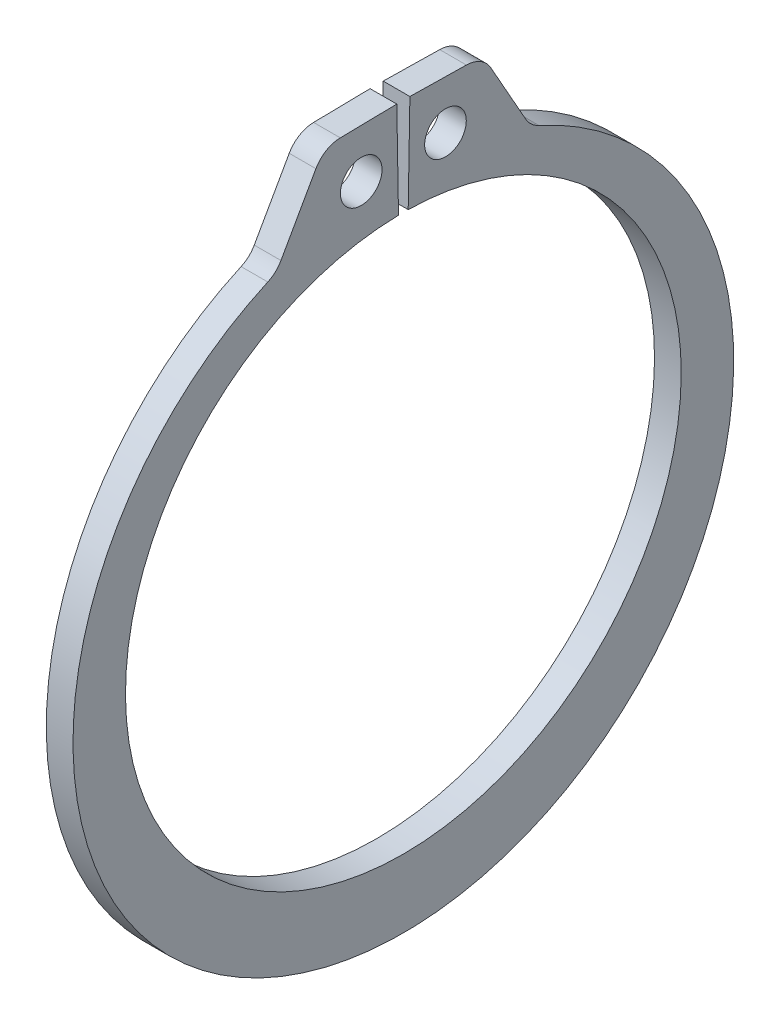
SolidWorks part; units mm, degrees
material "Cast Carbon Steel"
ref_plane "Front" through (0, 0, 0) normal (0, 0, 1) x (1, 0, 0)
ref_plane "Top" through (0, 0, 0) normal (0, 1, 0) x (1, 0, 0)
ref_plane "Right" through (0, 0, 0) normal (1, 0, 0) x (0, 0, -1)
sketch "Sketch1" plane through (0, 0, 0) normal (1, 0, 0) x (0, 0, -1)
  line L0 (0, 0) -> (0, 13.2207) construction
  line L1 (-0.2307, 13.2187) -> (-0.3114, 17.8408)
  line L2 (0.3114, 17.8408) -> (3.778, 17.7803)
  line L3 (3.778, 17.7803) -> (6.0478, 13.7531)
  line L4 (0.2307, 13.2187) -> (0.3114, 17.8408)
  line L5 (-0.3114, 17.8408) -> (-3.778, 17.7803)
  line L6 (-3.778, 17.7803) -> (-6.0478, 13.7531)
  line L7 (-6.0478, 13.7531) -> (-5.3219, 12.1023) construction
  line L8 (6.0478, 13.7531) -> (5.3219, 12.1023) construction
  line L9 (0, -13.2207) -> (0, -16.4719) construction
  line L10 (-3.778, 17.7803) -> (-0.2307, 13.2187) construction
  line L11 (0, 13.2207) -> (0, 17.8435) construction
  line L12 (-13.2207, 0) -> (13.2207, 0) construction
  circle A0 centre (0, 0) radius 13.2207 construction
  arc A1 (-0.2307, 13.2187) -> (0.2307, 13.2187) centre (0, 0) ccw
  circle A3 centre (0, 0) radius 19.304 construction
  circle A4 centre (-2.0044, 15.4995) radius 0.9906
  circle A5 centre (2.0044, 15.4995) radius 0.9906
  arc A6 (-6.0478, 13.7531) -> (6.0478, 13.7531) centre (0, -0.7543) ccw
  point P0 (0, -16.4719)
  dimension "A" = 26.4414
  dimension "Hole" = 1.9812
  dimension "Smin" = 1.8034
  dimension "H" = 4.6228
  dimension "D2" = 3.4671
  dimension "Angle" = 1
extrude "Extrude1" add sketch "Sketch1" along normal mid plane 1.27
fillet "Fillet1" radius 1.3589 4 edges at (0, 13.7531, 6.0478) (0, 13.7531, -6.0478) (0, 17.7803, 3.778) (0, 17.7803, -3.778)
sketch "Sketch2" plane through (0, 0, 0) normal (0, 0, 1) x (1, 0, 0)
  line L0 (-7.0612, 0) -> (18.3388, 0)
  line L1 (18.3388, 0) -> (18.3388, -14.2875)
  line L2 (-0.7112, -14.2875) -> (-6.223, -14.2875)
  line L3 (18.3388, -14.2875) -> (0.7112, -14.2875)
  line L4 (0.7112, -14.2875) -> (0.7112, -13.4493)
  line L5 (0.7112, -13.4493) -> (-0.7112, -13.4493)
  line L6 (-0.7112, -13.4493) -> (-0.7112, -14.2875)
  line L7 (-0.7112, -14.2875) -> (-7.0612, -14.2875) construction
  line L8 (-7.0612, -14.2875) -> (-7.0612, 0) construction
  line L9 (18.3388, 0) -> (76.391, 0) construction
  line L10 (-6.223, -14.2875) -> (-7.0612, -13.4493)
  line L11 (-7.0612, -13.4493) -> (-7.0612, 0)
  point P10 (0, -13.4493)
  dimension "D2" = 25.4
  dimension "D3" = 6.35
  dimension "D1" = 45
revolve "Revolve1" [suppressed] add sketch "Sketch2" angle 360 about L9
delete or keep bodies "Body-Delete1" [suppressed] type delete bodies bodies 122
equation "\"D2@Sketch2\" = \"D1@Extrude1\"*20"
equation "\"D3@Sketch2\" = \"D2@Sketch2\"/4"
equation "\"D2@Sketch1\" = \"H@Sketch1\"*.75"
